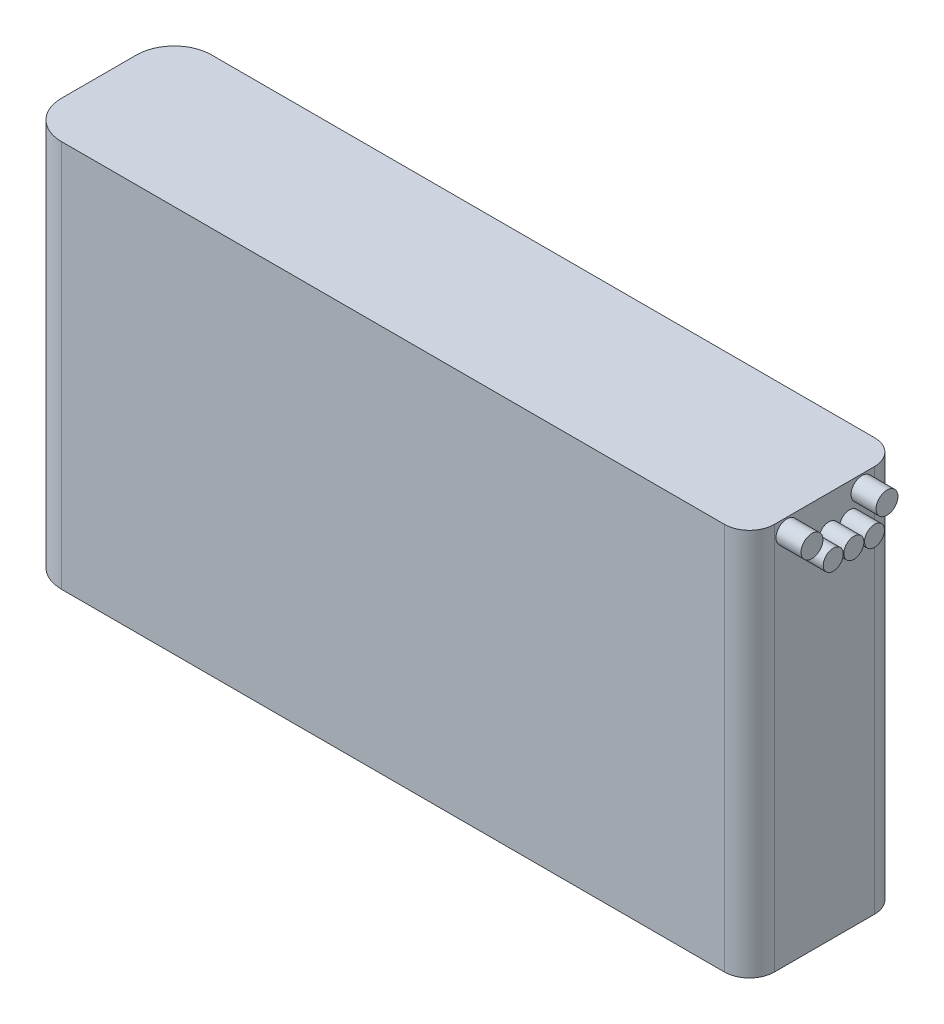
SolidWorks part; units mm, degrees
ref_plane "Ebene vorne" through (0, 0, 0) normal (0, 0, 1) x (1, 0, 0)
ref_plane "Ebene oben" through (0, 0, 0) normal (0, 1, 0) x (1, 0, 0)
ref_plane "Ebene rechts" through (0, 0, 0) normal (1, 0, 0) x (0, 0, -1)
sketch "Skizze1" plane through (0, 0, 0) normal (0, 0, 1) x (1, 0, 0)
  line L1 (0, 0) -> (58, 0)
  line L2 (0, 0) -> (0, 31)
  line L3 (0, 31) -> (58, 31)
  line L4 (58, 0) -> (58, 31)
  dimension "D1" = 58
  dimension "D2" = 31
extrude "Aufsatz-Linear austragen1" add sketch "Skizze1" along normal blind 12
fillet "Verrundung1" radius 2 2 edges at (58, 15.5, 0) (58, 15.5, 12)
fillet "Verrundung2" radius 3 2 edges at (0, 15.5, 12) (0, 15.5, 0)
sketch "Skizze3" plane through (58, 0, 0) normal (1, 0, 0) x (0, 0, -1)
  line L0 (-10, 31) -> (-2, 31) construction
  line L1 (0, 31) -> (0, 0) construction
  line L2 (-7.3, 28.2) -> (-5.65, 28.2) construction
  line L3 (-5.65, 28.2) -> (-4, 28.2) construction
  circle A0 centre (-9, 30) radius 0.875
  circle A1 centre (-3, 30) radius 0.875
  circle A2 centre (-4, 28.2) radius 0.8
  circle A3 centre (-5.65, 28.2) radius 0.8
  circle A4 centre (-7.3, 28.2) radius 0.8
  dimension "D1" = 1.75
  dimension "D6" = 1.6
  dimension "D2" = 1
  dimension "D3" = 6
  dimension "D4" = 3
  dimension "D5" = 1.65
  dimension "D7" = 4
  dimension "D8" = 1.8
extrude "Aufsatz-Linear austragen2" add sketch "Skizze3" along normal blind 2
